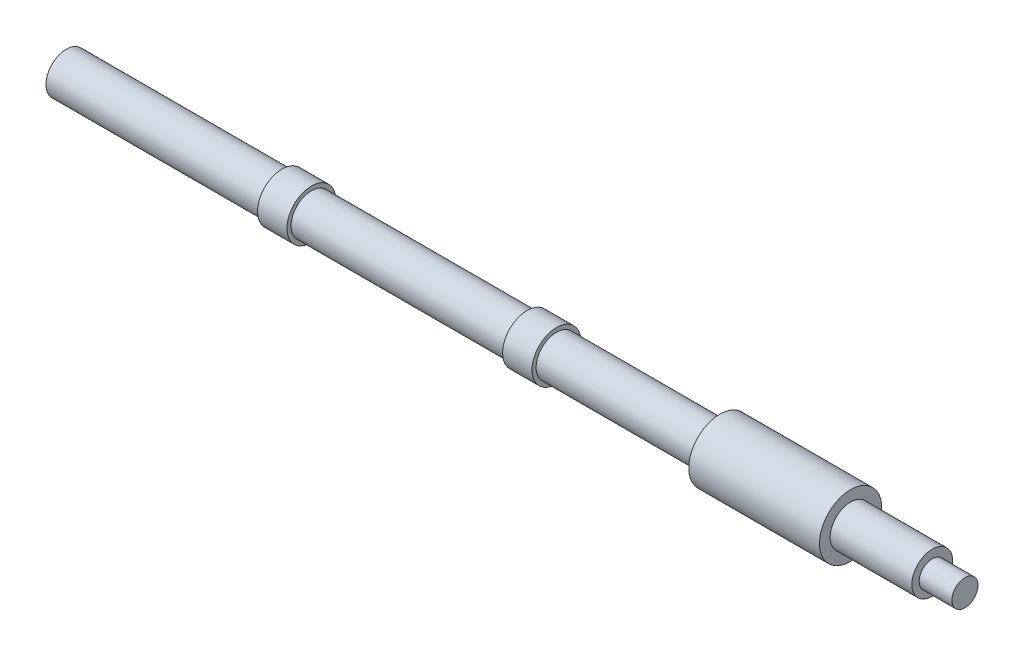
SolidWorks part; units mm, degrees
ref_plane "前视基准面" through (0, 0, 0) normal (0, 0, 1) x (1, 0, 0)
ref_plane "上视基准面" through (0, 0, 0) normal (0, 1, 0) x (1, 0, 0)
ref_plane "右视基准面" through (0, 0, 0) normal (1, 0, 0) x (0, 0, -1)
sketch "草图1" plane through (0, 0, 0) normal (1, 0, 0) x (0, 0, -1)
  circle A0 centre (0, 0) radius 12.5
extrude "凸台-拉伸1" add sketch "草图1" along normal blind 100 and the other way blind 50
sketch "草图2" plane through (100, 0, 0) normal (1, 0, 0) x (0, 0, -1)
  circle A0 centre (0, 0) radius 15
extrude "凸台-拉伸2" add sketch "草图2" against normal blind 18
sketch "草图3" plane through (100, 0, 0) normal (1, 0, 0) x (0, 0, -1)
  circle A0 centre (0, 0) radius 12.5
extrude "凸台-拉伸3" add sketch "草图3" along normal blind 132
sketch "草图4" plane through (232, 0, 0) normal (1, 0, 0) x (0, 0, -1)
  circle A0 centre (0, 0) radius 15
extrude "凸台-拉伸4" add sketch "草图4" along normal blind 18
sketch "草图5" plane through (250, 0, 0) normal (1, 0, 0) x (0, 0, -1)
  circle A0 centre (0, 0) radius 12.5
extrude "凸台-拉伸5" add sketch "草图5" along normal blind 100
sketch "草图6" plane through (350, 0, 0) normal (1, 0, 0) x (0, 0, -1)
  circle A0 centre (0, 0) radius 19.05
extrude "凸台-拉伸6" add sketch "草图6" along normal blind 80
sketch "草图7" plane through (430, 0, 0) normal (1, 0, 0) x (0, 0, -1)
  circle A0 centre (0, 0) radius 12.5
extrude "凸台-拉伸7" add sketch "草图7" along normal blind 50
sketch "草图9" plane through (480, 0, 0) normal (1, 0, 0) x (0, 0, -1)
  circle A0 centre (0, -0.6057) radius 8
extrude "凸台-拉伸8" add sketch "草图9" along normal blind 20
